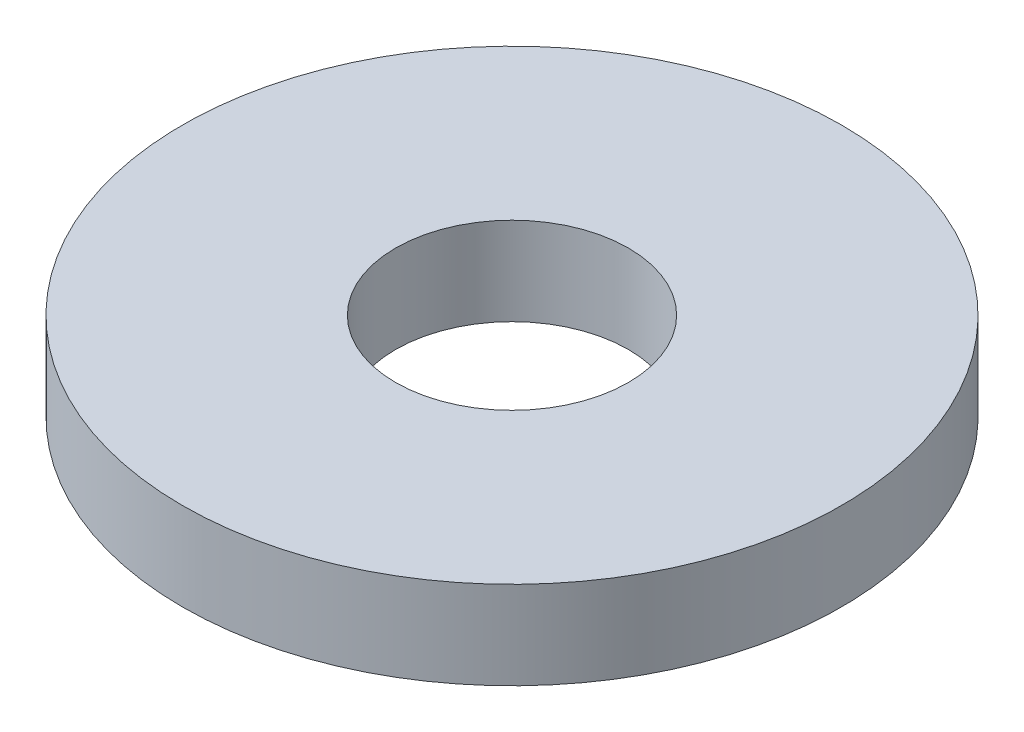
SolidWorks part; units mm, degrees
material "AISI 304"
ref_plane "Front Plane" through (0, 0, 0) normal (0, 0, 1) x (1, 0, 0)
ref_plane "Top Plane" through (0, 0, 0) normal (0, 1, 0) x (1, 0, 0)
ref_plane "Right Plane" through (0, 0, 0) normal (1, 0, 0) x (0, 0, -1)
sketch "Sketch1" plane through (0, 0, 0) normal (0, 1, 0) x (1, 0, 0)
  circle A0 centre (0, 0) radius 7.5
  circle A1 centre (0, 0) radius 2.65
  dimension "D1" = 5.3
  dimension "D2" = 15
extrude "Boss-Extrude1" add sketch "Sketch1" along normal blind 2
